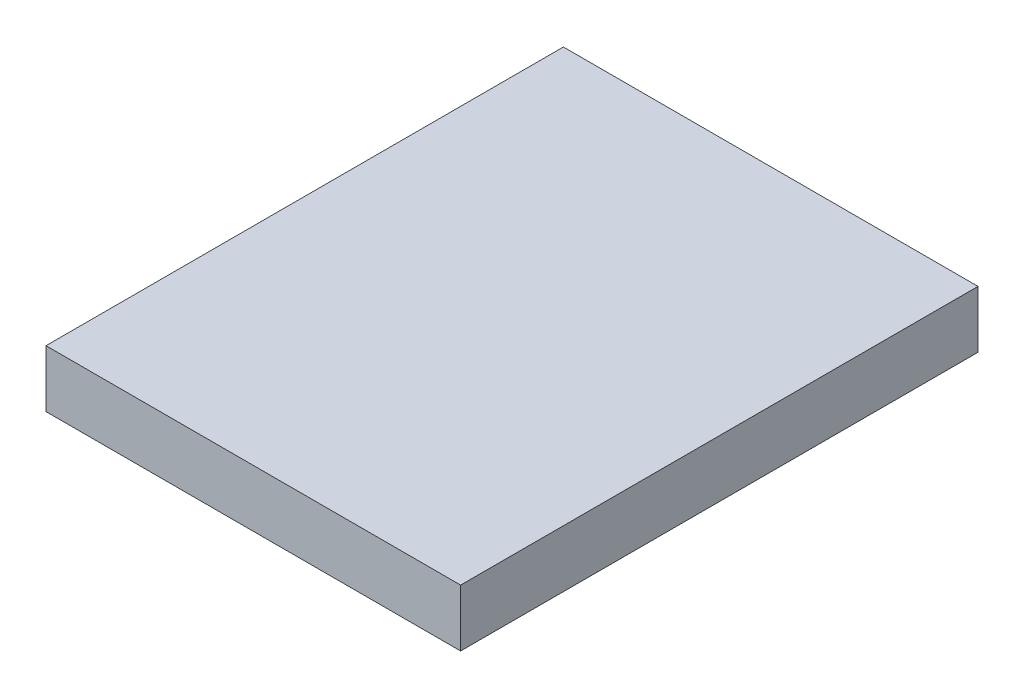
SolidWorks part; units mm, degrees
ref_plane "Front Plane" through (0, 0, 0) normal (0, 0, 1) x (1, 0, 0)
ref_plane "Top Plane" through (0, 0, 0) normal (0, 1, 0) x (1, 0, 0)
ref_plane "Right Plane" through (0, 0, 0) normal (1, 0, 0) x (0, 0, -1)
sketch "Sketch1" plane through (0, 0, 0) normal (0, 1, 0) x (1, 0, 0)
  line L1 (-5.81, 7.25) -> (5.81, 7.25)
  line L2 (-5.81, 7.25) -> (-5.81, -7.25)
  line L3 (-5.81, -7.25) -> (5.81, -7.25)
  line L4 (5.81, 7.25) -> (5.81, -7.25)
  line L5 (-5.81, 7.25) -> (5.81, -7.25) construction
  line L6 (-5.81, -7.25) -> (5.81, 7.25) construction
  point P0 (0, 0)
extrude "Boss-Extrude1" add sketch "Sketch1" along normal mid plane 1.6
